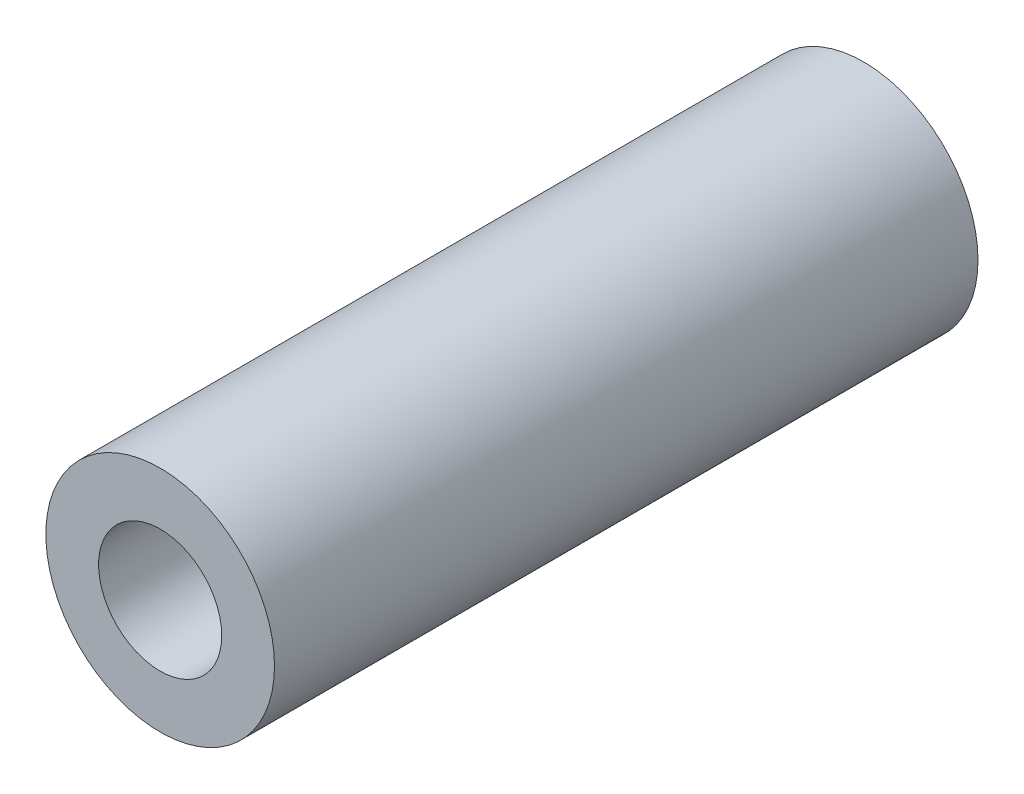
SolidWorks part; units mm, degrees
ref_plane "Front Plane" through (0, 0, 0) normal (0, 0, 1) x (1, 0, 0)
ref_plane "Top Plane" through (0, 0, 0) normal (0, 1, 0) x (1, 0, 0)
ref_plane "Right Plane" through (0, 0, 0) normal (1, 0, 0) x (0, 0, -1)
sketch "Sketch1" plane through (0, 0, 0) normal (0, 0, 1) x (1, 0, 0)
  circle A0 centre (0, 0) radius 3.25
  circle A1 centre (0, 0) radius 1.75
  dimension "D1" = 3.5
  dimension "D2" = 1.5
extrude "Boss-Extrude1" add sketch "Sketch1" along normal blind 20
